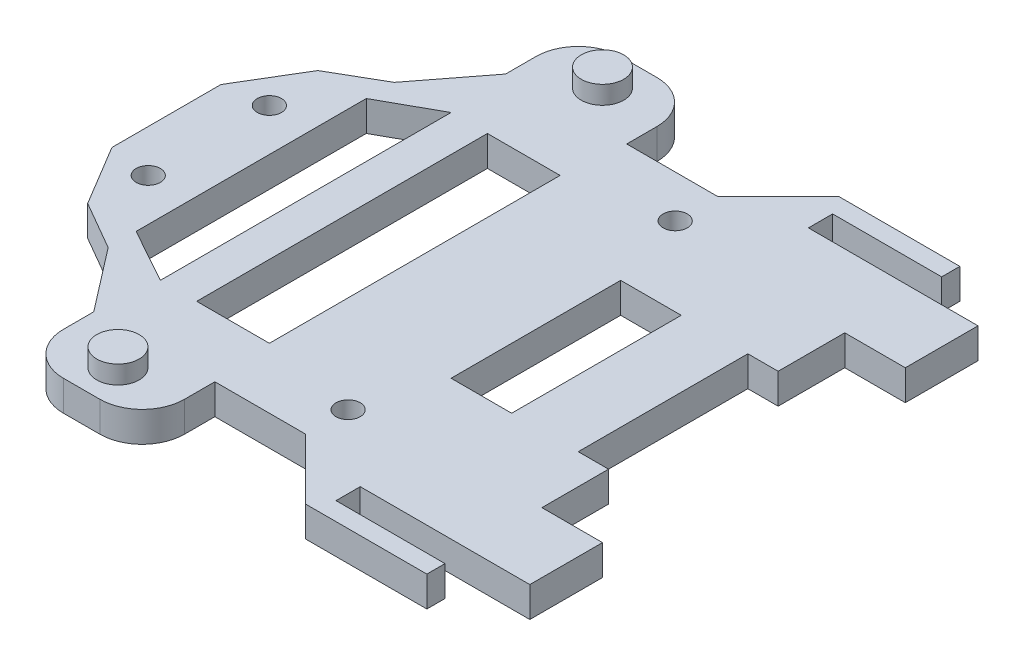
SolidWorks part; units mm, degrees
ref_plane "前视基准面" through (0, 0, 0) normal (0, 0, 1) x (1, 0, 0)
ref_plane "上视基准面" through (0, 0, 0) normal (0, 1, 0) x (1, 0, 0)
ref_plane "右视基准面" through (0, 0, 0) normal (1, 0, 0) x (0, 0, -1)
sketch "草图1" plane through (0, 0, 0) normal (0, 1, 0) x (1, 0, 0)
  line L0 (0, 0) -> (-11.0519, 0) construction
  line L1 (0, -9) -> (0, 9)
  line L2 (0, 9) -> (6, 19)
  line L3 (6, 19) -> (14, 23.6188)
  line L4 (14, 23.6188) -> (22, 34)
  line L5 (22, 34) -> (22, 46)
  line L6 (22, 46) -> (42, 46)
  line L7 (42, 46) -> (42, 34)
  line L8 (42, 34) -> (57, 34)
  line L9 (57, 34) -> (67, 44)
  line L10 (67, 44) -> (87, 44)
  line L11 (87, 44) -> (87, 41)
  line L12 (87, 41) -> (69, 41)
  line L13 (69, 41) -> (69, 37)
  line L14 (69, 37) -> (97, 37)
  line L15 (97, 37) -> (97, 25)
  line L16 (97, 25) -> (87, 25)
  line L17 (87, 25) -> (87, 14)
  line L18 (87, 14) -> (82, 14)
  line L19 (82, 14) -> (82, -14)
  line L20 (87, -14) -> (82, -14)
  line L21 (87, -25) -> (87, -14)
  line L22 (97, -25) -> (87, -25)
  line L23 (97, -37) -> (97, -25)
  line L24 (69, -37) -> (97, -37)
  line L25 (69, -41) -> (69, -37)
  line L26 (87, -41) -> (69, -41)
  line L27 (87, -44) -> (87, -41)
  line L28 (67, -44) -> (87, -44)
  line L29 (57, -34) -> (67, -44)
  line L30 (42, -34) -> (57, -34)
  line L31 (42, -46) -> (42, -34)
  line L32 (22, -46) -> (42, -46)
  line L33 (22, -34) -> (22, -46)
  line L34 (14, -23.6188) -> (22, -34)
  line L35 (6, -19) -> (14, -23.6188)
  line L36 (0, -9) -> (6, -19)
  point P2 (32, 46)
  point P7 (66.6977, 41.1976)
  point P25 (89.6225, 25.7963)
  point P26 (81.4951, 12.0513)
  point P28 (82, 0)
  point P45 (0, 0)
  dimension "D1" = 18
  dimension "D2" = 10
  dimension "D3" = 6
  dimension "D4" = 8
  dimension "D5" = 8
  dimension "D6" = 20
  dimension "D7" = 92
  dimension "D8" = 12
  dimension "D9" = 15
  dimension "D10" = 10
  dimension "D11" = 135
  dimension "D12" = 30
  dimension "D13" = 18
  dimension "D14" = 4
  dimension "D15" = 10
  dimension "D16" = 74
  dimension "D17" = 28
  dimension "D18" = 5
  dimension "D19" = 50
  dimension "D20" = 88
  dimension "D21" = 30
  dimension "D22" = 55
extrude "凸台-拉伸1" add sketch "草图1" along normal blind 5 contours L2 L3 L4 L5 L6 L7 L8 L9 L10 L11 L12 L13 L14 L15 L16 L17 L18 L19 L20 L21 L22 L23 L24 L25 L26 L27 L28 L29 L30 L31 L32 L33 L34 L35 L36 L1
sketch "草图2" plane through (0, 5, 0) normal (0, 1, 0) x (1, 0, 0)
  line L0 (32, 40) -> (32, 46) construction
  line L1 (22, 46) -> (42, 46) construction
  line L2 (87, -44) -> (87, -41) construction
  line L3 (-2.0997, 0) -> (46.7048, 0) construction
  line L4 (14, -19) -> (14, 19)
  line L5 (14, 19) -> (23, 24)
  line L6 (23, 24) -> (23, -24)
  line L7 (82, 14) -> (82, -14) construction
  line L8 (41, -24) -> (29, -24)
  line L9 (41, -24) -> (41, 24)
  line L10 (41, 24) -> (29, 24)
  line L11 (29, -24) -> (29, 24)
  line L12 (41, -24) -> (29, 24) construction
  line L13 (41, 24) -> (29, -24) construction
  line L14 (14, -19) -> (23, -24)
  line L15 (57, 27) -> (57, 34) construction
  line L17 (61, 14) -> (71, 14)
  line L18 (61, 14) -> (61, -14)
  line L19 (61, -14) -> (71, -14)
  line L20 (71, 14) -> (71, -14)
  line L21 (61, 14) -> (71, -14) construction
  line L22 (61, -14) -> (71, 14) construction
  circle A0 centre (32, 40) radius 3.5
  circle A1 centre (7, 10) radius 2
  circle A2 centre (32, -40) radius 3.5
  circle A3 centre (7, -10) radius 2
  circle A4 centre (57, 27) radius 2
  circle A5 centre (57, -27) radius 2
  point P14 (35, 0)
  point P27 (23, 0)
  point P28 (14, 0)
  point P35 (66, 0)
  dimension "D2" = 7
  dimension "D3" = 10
  dimension "D4" = 80
  dimension "D5" = 4
  dimension "D12" = 4
  dimension "D13" = 27
  dimension "D1" = 40
  dimension "D6" = 38
  dimension "D7" = 9
  dimension "D8" = 48
  dimension "D9" = 12
  dimension "D10" = 59
  dimension "D11" = 41
  dimension "D14" = 10
  dimension "D15" = 28
  dimension "D16" = 11
extrude "切除-拉伸1" cut sketch "草图2" against normal blind 44 contours L6 L14 L4 L5 | A1 | A3 | L9 L8 L11 L10 | L18 L17 L20 L19 | A5 | A4
sketch "草图3" plane through (0, 5, 0) normal (0, 1, 0) x (1, 0, 0)
  line L0 (32, 40) -> (32, 46) construction
  line L1 (22, 46) -> (42, 46) construction
  line L3 (-2.75, 0) -> (2.75, 0) construction
  circle A0 centre (32, 40) radius 3.5
  circle A1 centre (32, -40) radius 3.5
  dimension "D1" = 7
  dimension "D2" = 40
extrude "凸台-拉伸2" add sketch "草图3" along normal blind 3
fillet "圆角1" radius 7 4 edges at (22, 2.5, -46) (42, 2.5, -46) (42, 2.5, 46) (22, 2.5, 46)
